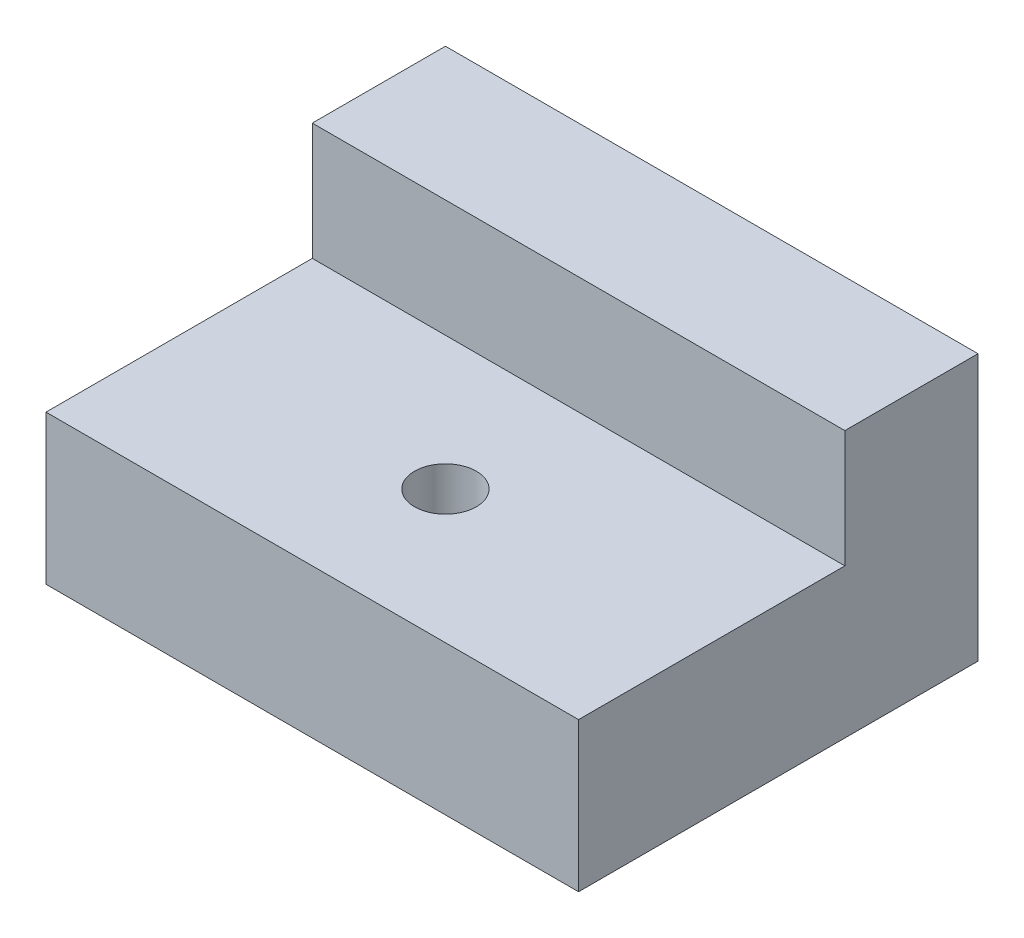
SolidWorks part; units mm, degrees
ref_plane "Front" through (0, 0, 0) normal (0, 0, 1) x (1, 0, 0)
ref_plane "Top" through (0, 0, 0) normal (0, 1, 0) x (1, 0, 0)
ref_plane "Right" through (0, 0, 0) normal (1, 0, 0) x (0, 0, -1)
sketch "Sketch1" plane through (0, 0, 0) normal (0, 1, 0) x (1, 0, 0)
  line L1 (0, 0) -> (25.4, 0)
  line L2 (0, 0) -> (0, 19.05)
  line L3 (0, 19.05) -> (25.4, 19.05)
  line L4 (25.4, 0) -> (25.4, 19.05)
  dimension "D1" = 19.05
  dimension "D2" = 25.4
extrude "Boss-Extrude1" add sketch "Sketch1" along normal blind 7.112
sketch "Sketch2" plane through (0, 7.112, 0) normal (0, 1, 0) x (1, 0, 0)
  line L0 (25.4, 0) -> (25.4, 19.05) construction
  line L1 (0, 19.05) -> (25.4, 19.05)
  line L2 (0, 19.05) -> (0, 12.7)
  line L3 (0, 12.7) -> (25.4, 12.7)
  line L4 (25.4, 19.05) -> (25.4, 12.7)
  dimension "D1" = 6.35
extrude "Boss-Extrude2" add sketch "Sketch2" along normal blind 5.588
hole_wizard "#32 (0.116) Diameter Hole1" positions "Sketch3" profile "Sketch4" hole size "#32" standard "ANSI Inch" end condition through all
sketch "Sketch3" plane through (0, 7.112, 0) normal (0, 1, 0) x (1, 0, 0)
  line L0 (0, 0) -> (25.4, 0) construction
  line L1 (0, 12.7) -> (0, 0) construction
  point P0 (12.7, 6.35)
  dimension "D1" = 6.35
  dimension "D2" = 12.7
sketch "Sketch4" plane through (12.7, 7.112, -6.35) normal (1, 0, 0) x (0, 0, 1)
  line L0 (0, 0) -> (0, 7.112)
  line L1 (0, 7.112) -> (1.4732, 7.112)
  line L2 (1.4732, 7.112) -> (1.4732, 0)
  line L5 (1.4732, 0) -> (0, 0)
  line L11 (0, -6.35) -> (0, 107.95) construction
  dimension "Thru Hole Dia." = 2.9464
  dimension "Thru Hole Depth" = 7.112
